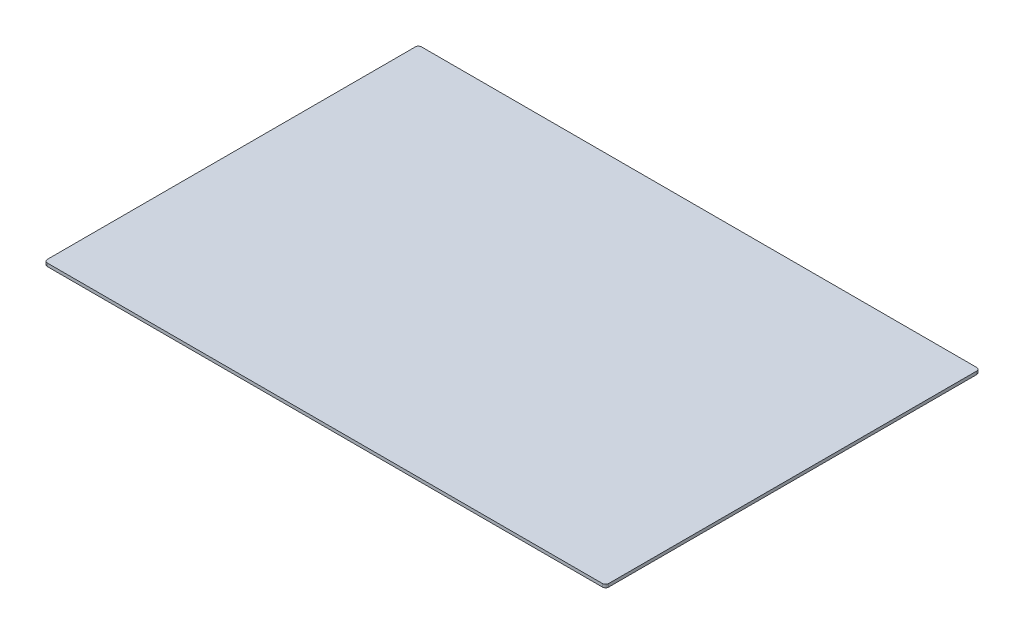
SolidWorks part; units mm, degrees
ref_plane "Front Plane" through (0, 0, 0) normal (0, 0, 1) x (1, 0, 0)
ref_plane "Top Plane" through (0, 0, 0) normal (0, 1, 0) x (1, 0, 0)
ref_plane "Right Plane" through (0, 0, 0) normal (1, 0, 0) x (0, 0, -1)
sketch "Sketch1" plane through (0, 0, 0) normal (0, 1, 0) x (1, 0, 0)
  line L1 (-450, 325) -> (450, 325)
  line L2 (-450, 325) -> (-450, -275)
  line L3 (-450, -275) -> (450, -275)
  line L4 (450, 325) -> (450, -275)
  point P0 (0, 0)
  dimension "D1" = 900
  dimension "D2" = 325
  dimension "D3" = 275
extrude "Boss-Extrude1" add sketch "Sketch1" along normal blind 5
fillet "Fillet2" radius 5 4 edges at (-450, 2.5, -325) (-450, 2.5, 275) (450, 2.5, -325) (450, 2.5, 275)
